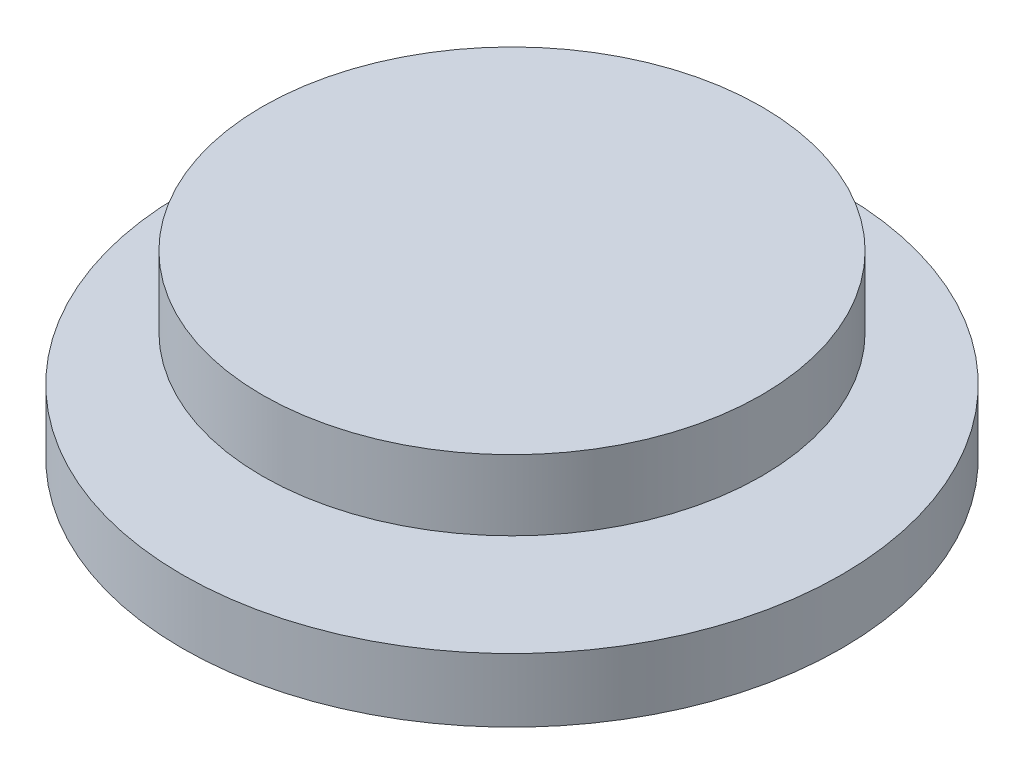
SolidWorks part; units mm, degrees
ref_plane "Front Plane" through (0, 0, 0) normal (0, 0, 1) x (1, 0, 0)
ref_plane "Top Plane" through (0, 0, 0) normal (0, 1, 0) x (1, 0, 0)
ref_plane "Right Plane" through (0, 0, 0) normal (1, 0, 0) x (0, 0, -1)
sketch "Sketch1" plane through (0, 0, 0) normal (0, 0, 1) x (1, 0, 0)
  line L0 (-28.0659, -31.9713) -> (-28.0659, 38.4909)
  line L1 (-28.0659, 38.4909) -> (29.8585, 38.4909)
  line L2 (29.8585, 38.4909) -> (29.8585, 22.1918)
  line L3 (29.8585, 22.1918) -> (0.8963, 22.1918)
  line L4 (0.8963, 22.1918) -> (0.8963, 11.6601)
  line L5 (0.8963, 11.6601) -> (48.4143, 11.6601)
  line L6 (48.4143, 11.6601) -> (48.4143, -3.1344)
  line L7 (48.4143, -3.1344) -> (0.8963, -15.9229)
  line L8 (0.8963, -15.9229) -> (0.8963, -31.9713)
  line L9 (0.8963, -31.9713) -> (-28.0659, -31.9713)
revolve "Revolve1" add sketch "Sketch1" angle 360 about L0
